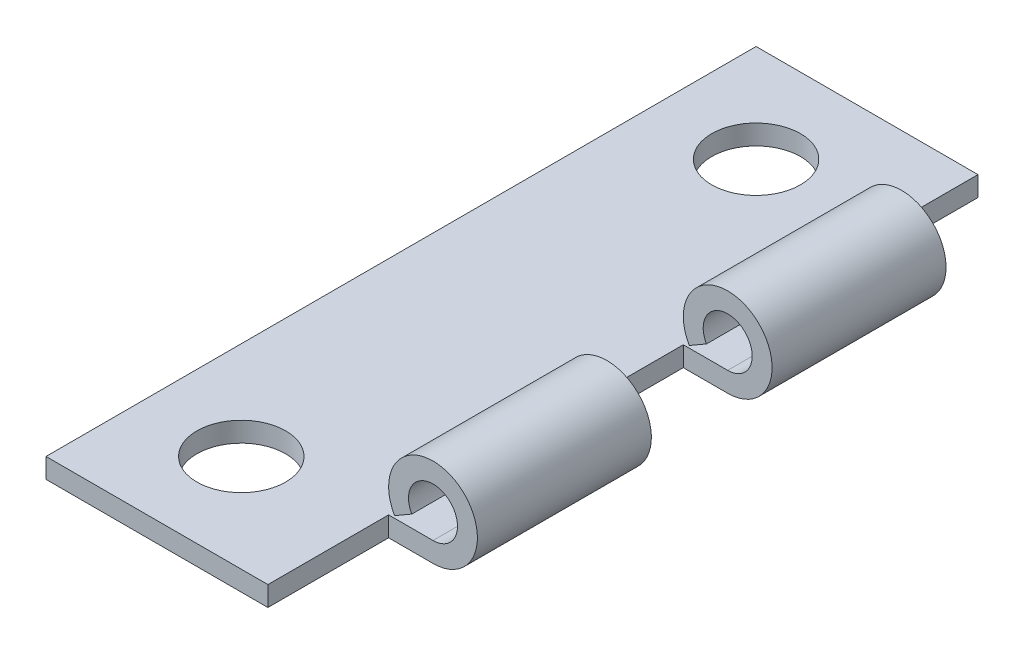
SolidWorks part; units mm, degrees
ref_plane "Front Plane" through (0, 0, 0) normal (0, 0, 1) x (1, 0, 0)
ref_plane "Top Plane" through (0, 0, 0) normal (0, 1, 0) x (1, 0, 0)
ref_plane "Right Plane" through (0, 0, 0) normal (1, 0, 0) x (0, 0, -1)
sketch "Sketch1" plane through (0, 0, 0) normal (0, 0, 1) x (1, 0, 0)
  line L0 (0, 0) -> (19.05, 0)
  line L1 (16.3004, 1.5875) -> (17.5322, 2.2987)
  line L2 (19.05, 1.4224) -> (0, 1.4224)
  line L3 (0, 1.4224) -> (0, 0)
  line L4 (19.05, 1.4224) -> (19.05, 10.3225) construction
  arc A0 (19.05, 0) -> (16.3004, 1.5875) centre (19.05, 3.175) ccw
  arc A1 (17.5322, 2.2987) -> (19.05, 1.4224) centre (19.05, 3.175) cw
  dimension "D1" = 1.4224
  dimension "D3" = 120
  dimension "D5" = 3.175
  dimension "D2" = 1.4224
  dimension "D4" = 19.05
extrude "Boss-Extrude1" add sketch "Sketch1" along normal blind 50.8
sketch "Sketch2" plane through (0, 0, 0) normal (0, -1, 0) x (1, 0, 0)
  line L0 (0, 50.8) -> (0, 0) construction
  line L1 (0, 50.8) -> (19.05, 50.8) construction
  line L2 (0, 0) -> (19.05, 0) construction
  line L3 (22.225, 0) -> (22.225, 50.8) construction
  line L4 (15.875, 50.8) -> (22.225, 50.8)
  line L5 (15.875, 50.8) -> (15.875, 42.164)
  line L6 (15.875, 42.164) -> (22.225, 42.164)
  line L7 (22.225, 50.8) -> (22.225, 42.164)
  line L8 (8.0066, 50.8) -> (8.0066, 0) construction
  line L9 (22.225, 29.718) -> (15.875, 29.718)
  line L10 (22.225, 29.718) -> (22.225, 21.082)
  line L11 (22.225, 21.082) -> (15.875, 21.082)
  line L12 (15.875, 29.718) -> (15.875, 21.082)
  line L13 (22.225, 8.636) -> (15.875, 8.636)
  line L14 (22.225, 8.636) -> (22.225, 0)
  line L15 (22.225, 0) -> (15.875, 0)
  line L16 (15.875, 8.636) -> (15.875, 0)
  line L17 (22.225, 25.4) -> (8.0066, 25.4) construction
  circle A0 centre (6.985, 43.815) radius 3.175
  circle A1 centre (6.985, 6.985) radius 3.175
  dimension "D1" = 6.985
  dimension "D4" = 6.35
  dimension "D2" = 6.985
  dimension "D3" = 6.985
  dimension "D5" = 50.8
  dimension "D6" = 8.636
  dimension "D7" = 6.35
extrude "Cut-Extrude1" cut sketch "Sketch2" against normal through all
equation "\"D2@Sketch1\"=\"D1@Sketch1\""
equation "\"D2@Sketch2\"=\"D1@Sketch2\""
equation "\"D3@Sketch2\"=\"D1@Sketch2\""
